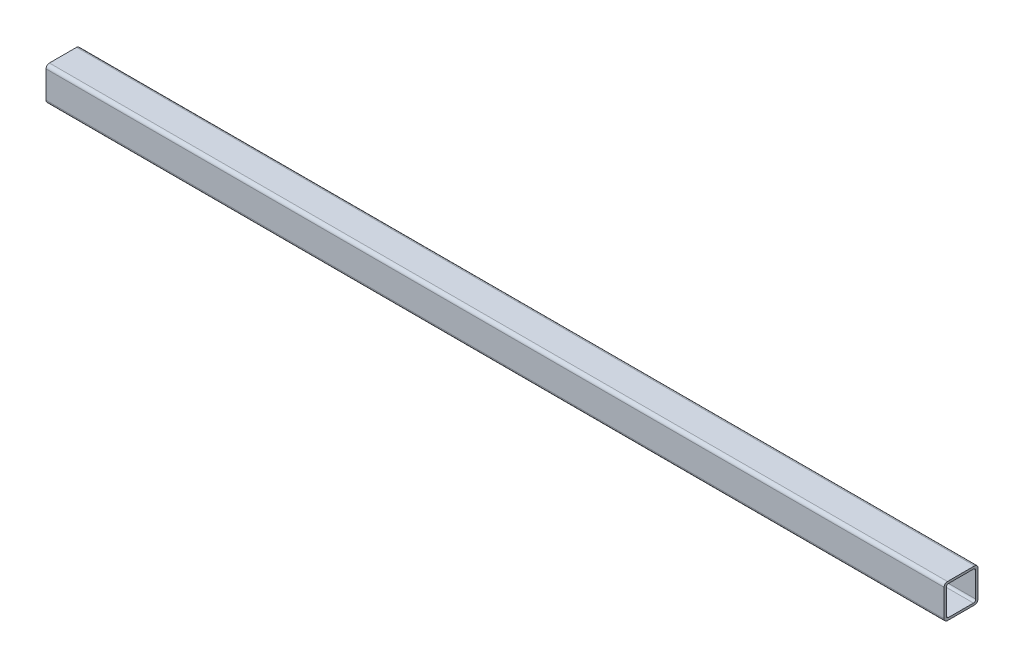
SolidWorks part; units mm, degrees
material "СТ3КП"
ref_plane "Спереди" through (0, 0, 0) normal (0, 0, 1) x (1, 0, 0)
ref_plane "Сверху" through (0, 0, 0) normal (0, 1, 0) x (1, 0, 0)
ref_plane "Справа" through (0, 0, 0) normal (1, 0, 0) x (0, 0, -1)
sketch "Эскиз1" plane through (0, 0, 0) normal (1, 0, 0) x (0, 0, -1)
  line L0 (-30, 0) -> (270, 0) construction
  line L1 (0, 0) -> (0, 28.5) construction
  line B0 (3, 30) -> (27, 30)
  line B1 (0, 27) -> (0, 3)
  line B2 (3, 0) -> (27, 0)
  line B3 (30, 27) -> (30, 3)
  line B4 (4, 28) -> (26, 28)
  line B5 (2, 26) -> (2, 4)
  line B6 (4, 2) -> (26, 2)
  line B7 (28, 26) -> (28, 4)
  arc B8 (0, 3) -> (3, 0) centre (3, 3) ccw
  arc B9 (27, 0) -> (30, 3) centre (27, 3) ccw
  arc B10 (27, 30) -> (30, 27) centre (27, 27) cw
  arc B11 (3, 30) -> (0, 27) centre (3, 27) ccw
  arc B12 (2, 4) -> (4, 2) centre (4, 4) ccw
  arc B13 (26, 2) -> (28, 4) centre (26, 4) ccw
  arc B14 (26, 28) -> (28, 26) centre (26, 26) cw
  arc B15 (4, 28) -> (2, 26) centre (4, 26) ccw
sketch_block_instance "Блок-30х30х2-1"
sketch_block "Блок-30х30х2" parameters "D3"=3, "D4"=2, "D1"=30, "D2"=2
extrude "Бобышка-Вытянуть1" add sketch "Эскиз1" against normal up to surface (397 mm away)
mirror "Зеркальное отражение2" about plane through (0, 3, -3) normal (1, 0, 0) of bodies 103
